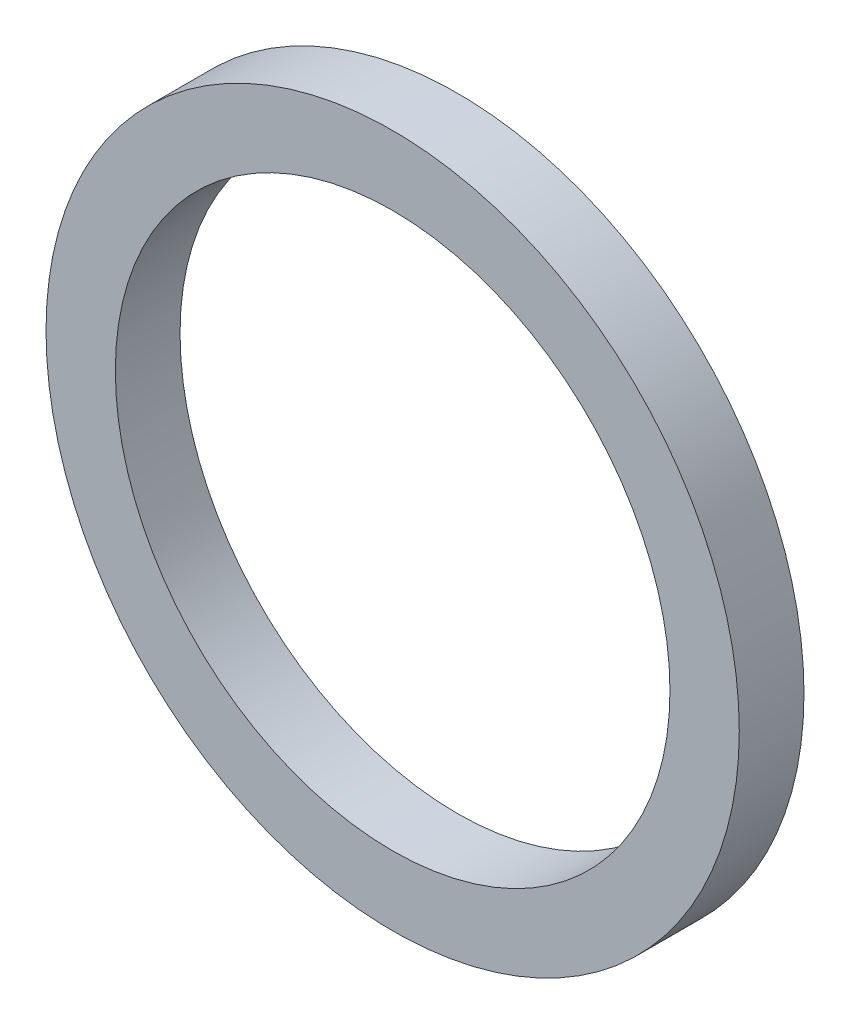
SolidWorks part; units mm, degrees
ref_plane "前视基准面" through (0, 0, 0) normal (0, 0, 1) x (1, 0, 0)
ref_plane "上视基准面" through (0, 0, 0) normal (0, 1, 0) x (1, 0, 0)
ref_plane "右视基准面" through (0, 0, 0) normal (1, 0, 0) x (0, 0, -1)
other "Configuration Table"
sketch "草图1" plane through (0, 0, 0) normal (0, 0, 1) x (1, 0, 0)
  circle A0 centre (0, 0) radius 30
  circle A1 centre (0, 0) radius 37.5
  dimension "D1" = 60
  dimension "D2" = 75
extrude "凸台-拉伸1" add sketch "草图1" along normal blind 7
